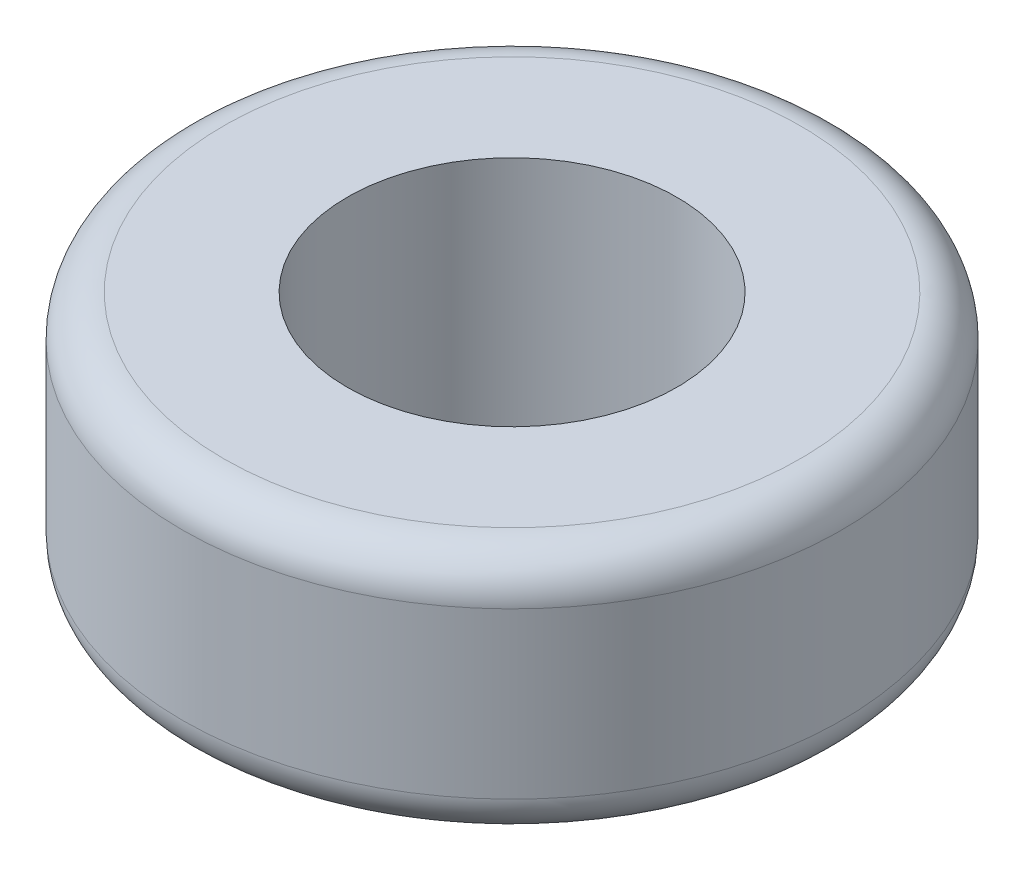
SolidWorks part; units mm, degrees
ref_plane "前视基准面" through (0, 0, 0) normal (0, 0, 1) x (1, 0, 0)
ref_plane "上视基准面" through (0, 0, 0) normal (0, 1, 0) x (1, 0, 0)
ref_plane "右视基准面" through (0, 0, 0) normal (1, 0, 0) x (0, 0, -1)
sketch "Sketch1" plane through (0, 0, 0) normal (0, 1, 0) x (1, 0, 0)
  circle A0 centre (0, 0) radius 2
  circle A1 centre (0, 0) radius 4
extrude "Boss-Extrude1" add sketch "Sketch1" along normal blind 3
fillet "Fillet1" radius 0.5 2 edges at (0, 0, 4) (0, 3, 4)
